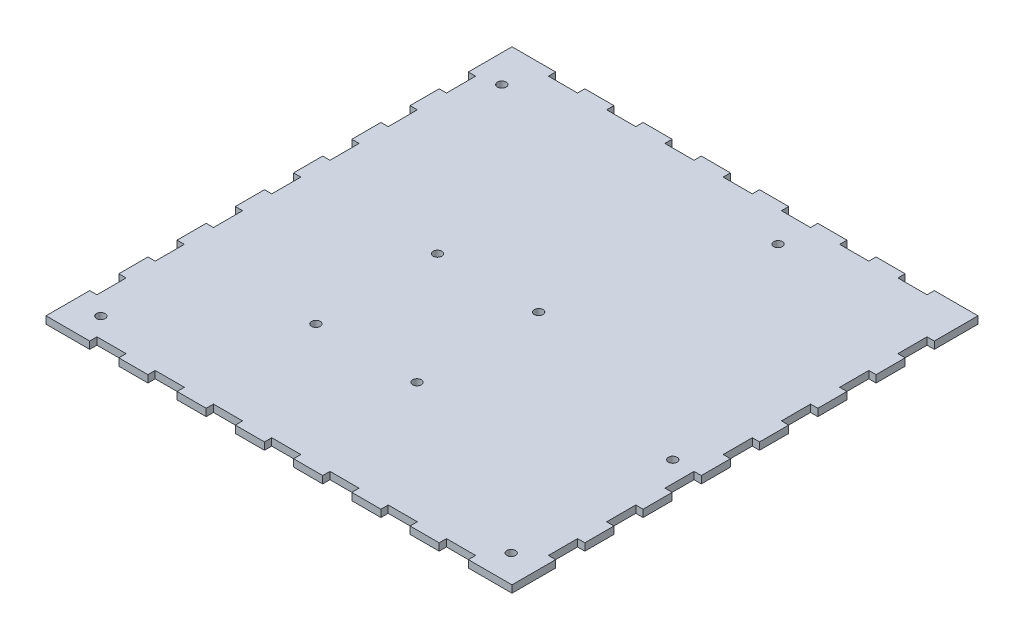
SolidWorks part; units mm, degrees
material "Oak"
ref_plane "Front Plane" through (0, 0, 0) normal (0, 0, 1) x (1, 0, 0)
ref_plane "Top Plane" through (0, 0, 0) normal (0, 1, 0) x (1, 0, 0)
ref_plane "Right Plane" through (0, 0, 0) normal (1, 0, 0) x (0, 0, -1)
sketch "Sketch1" plane through (0, 0, 0) normal (0, 1, 0) x (1, 0, 0)
  line L1 (80, 80) -> (-80, 80)
  line L2 (80, 80) -> (80, -80)
  line L3 (80, -80) -> (-80, -80)
  line L4 (-80, 80) -> (-80, -80)
  line L5 (80, 80) -> (-80, -80) construction
  line L6 (80, -80) -> (-80, 80) construction
  point P0 (0, 0)
  dimension "D1" = 160
extrude "Boss-Extrude1" add sketch "Sketch1" along normal mid plane 2.5
sketch "Sketch3" plane through (0, 1.25, 0) normal (0, 1, 0) x (1, 0, 0)
  line L1 (77.5, 77.5) -> (-77.5, 77.5)
  line L2 (77.5, 77.5) -> (77.5, -77.5)
  line L3 (77.5, -77.5) -> (-77.5, -77.5)
  line L4 (-77.5, 77.5) -> (-77.5, -77.5)
  line L5 (77.5, 77.5) -> (-77.5, -77.5) construction
  line L6 (77.5, -77.5) -> (-77.5, 77.5) construction
  line L7 (80, -35) -> (77.5, -35)
  line L11 (80, -80) -> (80, 80) construction
  line L12 (80, -55) -> (77.5, -55)
  line L13 (80, -55) -> (80, -65)
  line L14 (80, -65) -> (77.5, -65)
  line L15 (77.5, -55) -> (77.5, -65)
  line L16 (80, -35) -> (80, -45)
  line L17 (77.5, -35) -> (77.5, -45)
  line L18 (80, -45) -> (77.5, -45)
  line L19 (80, -15) -> (77.5, -15)
  line L20 (80, -15) -> (80, -25)
  line L21 (77.5, -15) -> (77.5, -25)
  line L22 (80, -25) -> (77.5, -25)
  line L23 (80, 5) -> (77.5, 5)
  line L24 (80, 5) -> (80, -5)
  line L25 (77.5, 5) -> (77.5, -5)
  line L26 (80, -5) -> (77.5, -5)
  line L27 (80, 25) -> (77.5, 25)
  line L28 (80, 25) -> (80, 15)
  line L29 (77.5, 25) -> (77.5, 15)
  line L30 (80, 15) -> (77.5, 15)
  line L31 (80, 45) -> (77.5, 45)
  line L32 (80, 45) -> (80, 35)
  line L33 (77.5, 45) -> (77.5, 35)
  line L34 (80, 35) -> (77.5, 35)
  line L35 (80, 65) -> (77.5, 65)
  line L36 (80, 65) -> (80, 55)
  line L37 (77.5, 65) -> (77.5, 55)
  line L38 (80, 55) -> (77.5, 55)
  line L39 (80, -55) -> (80, -35) construction
  line L40 (-65, 80) -> (-65, 77.5)
  line L41 (-55, 77.5) -> (-65, 77.5)
  line L42 (-55, 80) -> (-55, 77.5)
  line L43 (-55, 80) -> (-65, 80)
  line L44 (-35, 80) -> (-45, 80)
  line L45 (-45, 80) -> (-45, 77.5)
  line L46 (-35, 77.5) -> (-45, 77.5)
  line L47 (-35, 80) -> (-35, 77.5)
  line L48 (-15, 80) -> (-25, 80)
  line L49 (-25, 80) -> (-25, 77.5)
  line L50 (-15, 77.5) -> (-25, 77.5)
  line L51 (-15, 80) -> (-15, 77.5)
  line L52 (5, 80) -> (-5, 80)
  line L53 (-5, 80) -> (-5, 77.5)
  line L54 (5, 77.5) -> (-5, 77.5)
  line L55 (5, 80) -> (5, 77.5)
  line L56 (25, 80) -> (15, 80)
  line L57 (15, 80) -> (15, 77.5)
  line L58 (25, 77.5) -> (15, 77.5)
  line L59 (25, 80) -> (25, 77.5)
  line L60 (45, 80) -> (35, 80)
  line L61 (35, 80) -> (35, 77.5)
  line L62 (45, 77.5) -> (35, 77.5)
  line L63 (45, 80) -> (45, 77.5)
  line L64 (65, 80) -> (55, 80)
  line L65 (55, 80) -> (55, 77.5)
  line L66 (65, 77.5) -> (55, 77.5)
  line L67 (65, 80) -> (65, 77.5)
  line L68 (65, -80) -> (65, -77.5)
  line L69 (55, -77.5) -> (65, -77.5)
  line L70 (55, -80) -> (55, -77.5)
  line L71 (55, -80) -> (65, -80)
  line L72 (35, -80) -> (45, -80)
  line L73 (45, -80) -> (45, -77.5)
  line L74 (35, -77.5) -> (45, -77.5)
  line L75 (35, -80) -> (35, -77.5)
  line L76 (15, -80) -> (25, -80)
  line L77 (25, -80) -> (25, -77.5)
  line L78 (15, -77.5) -> (25, -77.5)
  line L79 (15, -80) -> (15, -77.5)
  line L80 (-5, -80) -> (5, -80)
  line L81 (5, -80) -> (5, -77.5)
  line L82 (-5, -77.5) -> (5, -77.5)
  line L83 (-5, -80) -> (-5, -77.5)
  line L84 (-25, -80) -> (-15, -80)
  line L85 (-15, -80) -> (-15, -77.5)
  line L86 (-25, -77.5) -> (-15, -77.5)
  line L87 (-25, -80) -> (-25, -77.5)
  line L88 (-45, -80) -> (-35, -80)
  line L89 (-35, -80) -> (-35, -77.5)
  line L90 (-45, -77.5) -> (-35, -77.5)
  line L91 (-45, -80) -> (-45, -77.5)
  line L92 (-65, -80) -> (-55, -80)
  line L93 (-55, -80) -> (-55, -77.5)
  line L94 (-65, -77.5) -> (-55, -77.5)
  line L95 (-65, -80) -> (-65, -77.5)
  line L96 (-80, -65) -> (-77.5, -65)
  line L97 (-77.5, -65) -> (-77.5, -55)
  line L98 (-80, -55) -> (-77.5, -55)
  line L99 (-80, -65) -> (-80, -55)
  line L100 (-80, -45) -> (-77.5, -45)
  line L101 (-77.5, -45) -> (-77.5, -35)
  line L102 (-80, -35) -> (-77.5, -35)
  line L103 (-80, -45) -> (-80, -35)
  line L104 (-80, -25) -> (-77.5, -25)
  line L105 (-77.5, -25) -> (-77.5, -15)
  line L106 (-80, -15) -> (-77.5, -15)
  line L107 (-80, -25) -> (-80, -15)
  line L108 (-80, -5) -> (-77.5, -5)
  line L109 (-77.5, -5) -> (-77.5, 5)
  line L110 (-80, 5) -> (-77.5, 5)
  line L111 (-80, -5) -> (-80, 5)
  line L112 (-80, 15) -> (-77.5, 15)
  line L113 (-77.5, 15) -> (-77.5, 25)
  line L114 (-80, 25) -> (-77.5, 25)
  line L115 (-80, 15) -> (-80, 25)
  line L116 (-80, 35) -> (-77.5, 35)
  line L117 (-77.5, 35) -> (-77.5, 45)
  line L118 (-80, 45) -> (-77.5, 45)
  line L119 (-80, 35) -> (-80, 45)
  line L120 (-80, 55) -> (-80, 65)
  line L121 (-80, 55) -> (-77.5, 55)
  line L122 (-77.5, 55) -> (-77.5, 65)
  line L123 (-80, 65) -> (-77.5, 65)
  point P0 (0, 0)
  point P12 (80, 0)
  line M18 (-80, 80) -> (-80, -80)
  line M19 (-80, -80) -> (80, -80)
  line M20 (80, -80) -> (80, 80)
  line M21 (80, 80) -> (-80, 80)
  dimension "D1" = 155
  dimension "D2" = 10
  dimension "D4" = 20
  dimension "D3" = 7
extrude "Cut-Extrude2" cut sketch "Sketch3" against normal through all contours L123 L121 L4 M18 | L118 L116 L4 M18 | L114 L112 L4 M18 | L110 L108 L4 M18 | L106 L104 L4 M18 | L102 L100 L4 M18 | L98 L96 L4 M18 | L95 L93 L3 M19 | L91 L89 L3 M19 | L87 L85 L3 M19 | L83 L81 L3 M19 | L79 L77 L3 M19 | L75 L73 L3 M19 | L70 L68 L3 M19 | L14 L12 L2 M20 | L34 L31 L2 M20 | L30 L27 L2 M20 | L26 L23 L2 M20 | L22 L19 L2 M20 | L18 L7 L2 M20 | L67 L65 L1 M21 | L63 L61 L1 M21 | L59 L57 L1 M21 | L55 L53 L1 M21 | L51 L49 L1 M21 | L47 L45 L1 M21 | L42 L40 L1 M21 | L36 L38 L37 L35
sketch "Sketch2" plane through (0, 1.25, 0) normal (0, 1, 0) x (1, 0, 0)
  circle A0 centre (24.3548, 67) radius 1.5 construction
  circle A1 centre (-70.5, 67) radius 1.5 construction
  circle A2 centre (70.3823, -15.199) radius 1.5 construction
  circle A3 centre (-31.2521, 5.6768) radius 1.5 construction
  circle A4 centre (3.4574, 5.6768) radius 1.5 construction
  circle A5 centre (3.4574, -36.0749) radius 1.5 construction
  circle A6 centre (-70.5, -70.6726) radius 1.5 construction
  circle A7 centre (24.3548, 67) radius 1.5
  circle A8 centre (-70.5, 67) radius 1.5
  circle A9 centre (70.3823, -15.199) radius 1.5
  circle A10 centre (-31.2521, 5.6768) radius 1.5
  circle A11 centre (3.4574, 5.6768) radius 1.5
  circle A12 centre (3.4574, -36.0749) radius 1.5
  circle A13 centre (-70.5, -70.6726) radius 1.5
  circle A14 centre (-31.2521, -36.0749) radius 1.5 construction
  circle A15 centre (-31.2521, -36.0749) radius 1.5
  circle A16 centre (70.3823, -70.6726) radius 1.5 construction
  circle A17 centre (70.3823, -70.6726) radius 1.5
extrude "Cut-Extrude1" cut sketch "Sketch2" against normal through all
equation "\"thick\"= 0.25"
equation "\"D1@Boss-Extrude1\"=\"thick\""
equation "\"hole_length\"= 1"
equation "\"length\"= 16"
equation "\"D1@Sketch1\"=\"length\""
equation "\"D2@Sketch3\"=\"hole_length\""
